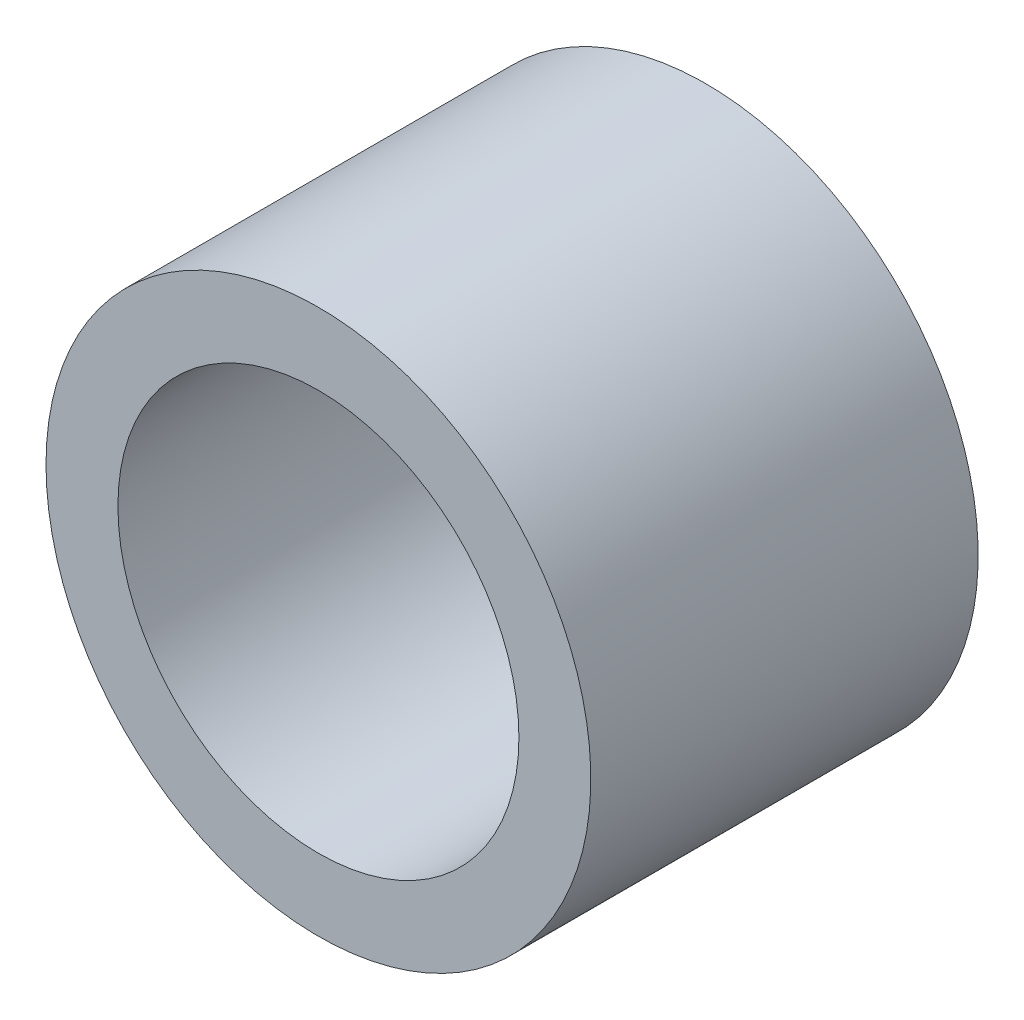
SolidWorks part; units mm, degrees
ref_plane "Front Plane" through (0, 0, 0) normal (0, 0, 1) x (1, 0, 0)
ref_plane "Top Plane" through (0, 0, 0) normal (0, 1, 0) x (1, 0, 0)
ref_plane "Right Plane" through (0, 0, 0) normal (1, 0, 0) x (0, 0, -1)
sketch "Sketch1" plane through (0, 0, 0) normal (0, 0, 1) x (1, 0, 0)
  circle A0 centre (0, 0) radius 4.0894
  circle A1 centre (0, 0) radius 5.5562
  dimension "D1" = 11.1125
  dimension "D2" = 8.1788
extrude "Boss-Extrude1" add sketch "Sketch1" along normal up to surface (7.9 mm away)
